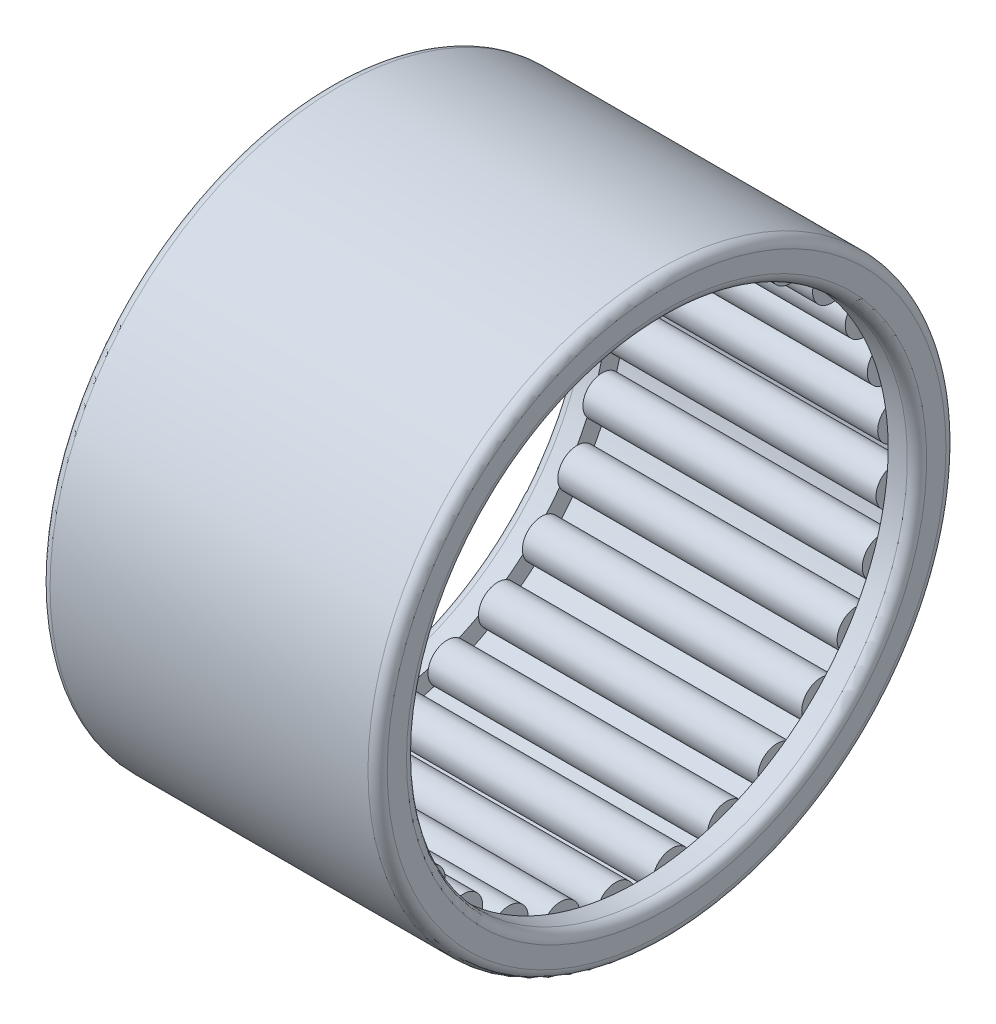
SolidWorks part; units mm, degrees
material "Plain Carbon Steel"
ref_plane "Front Plane" through (0, 0, 0) normal (0, 0, 1) x (1, 0, 0)
ref_plane "Top Plane" through (0, 0, 0) normal (0, 1, 0) x (1, 0, 0)
ref_plane "Right Plane" through (0, 0, 0) normal (1, 0, 0) x (0, 0, -1)
sketch "Sketch1" plane through (0, 0, 0) normal (0, 0, 1) x (1, 0, 0)
  line L0 (-17.5, 26) -> (-17.5, 30)
  line L1 (-17.5, 30) -> (17.5, 30)
  line L2 (17.5, 30) -> (17.5, 26)
  line L3 (17.5, 26) -> (14.5, 26)
  line L4 (14.5, 26) -> (14.5, 28)
  line L5 (14.5, 28) -> (-14.5, 28)
  line L6 (-14.5, 28) -> (-14.5, 26)
  line L7 (-14.5, 26) -> (-17.5, 26)
  line L8 (0, 0) -> (33.7186, 0) construction
  point P7 (0, 30)
  dimension "D1" = 4
  dimension "D2" = 35
  dimension "D3" = 4
  dimension "D4" = 3
  dimension "D5" = 2
  dimension "D6" = 30
  dimension "D7" = 3
revolve "Revolve1" add sketch "Sketch1" angle 360 about L8
fillet "Fillet1" radius 1 4 edges at (-17.5, 0, 30) (-17.5, 0, 26) (17.5, 0, 26) (17.5, 0, 30)
scale "Scale1" bodies to scale 103 120 114 108 125 102 119 113 107 124 101 130 118 112 129 106 123 117 111 128 105 122 116 110 127 104 121 115 109 126 scale about centroid uniform scaling yes scale factor 0.625
sketch "Sketch6" plane through (0, 0, 0) normal (1, 0, 0) x (0, 0, -1)
  line L0 (0, 0) -> (-16.8673, 0.5111) construction
  circle A0 centre (-16.8673, 0.5111) radius 1.25
  circle A1 centre (0, 0) radius 16.875 construction
  circle A2 centre (-16.363, 4.1251) radius 1.25
  circle A3 centre (-15.0937, 7.5462) radius 1.25
  circle A4 centre (-13.1186, 10.6145) radius 1.25
  circle A5 centre (-10.5301, 13.1864) radius 1.25
  circle A6 centre (-7.4492, 15.1418) radius 1.25
  circle A7 centre (-4.02, 16.3892) radius 1.25
  circle A8 centre (-0.4029, 16.8702) radius 1.25
  circle A9 centre (3.2332, 16.5624) radius 1.25
  circle A10 centre (6.718, 15.4801) radius 1.25
  circle A11 centre (9.8887, 13.674) radius 1.25
  circle A12 centre (12.597, 11.2286) radius 1.25
  circle A13 centre (14.7163, 8.2581) radius 1.25
  circle A14 centre (16.1475, 4.9014) radius 1.25
  circle A15 centre (16.8236, 1.3156) radius 1.25
  circle A16 centre (16.7131, -2.3317) radius 1.25
  circle A17 centre (15.8211, -5.8701) radius 1.25
  circle A18 centre (14.1893, -9.1339) radius 1.25
  circle A19 centre (11.8941, -11.9706) radius 1.25
  circle A20 centre (9.0427, -14.2476) radius 1.25
  circle A21 centre (5.7684, -15.8585) radius 1.25
  circle A22 centre (2.2245, -16.7277) radius 1.25
  circle A23 centre (-1.4235, -16.8149) radius 1.25
  circle A24 centre (-5.0049, -16.1157) radius 1.25
  circle A25 centre (-8.3523, -14.663) radius 1.25
  circle A26 centre (-11.3091, -12.5247) radius 1.25
  circle A27 centre (-13.7372, -9.8008) radius 1.25
  circle A28 centre (-15.5229, -6.6185) radius 1.25
  circle A29 centre (-16.5828, -3.1268) radius 1.25
  point P66 (0, 0)
  dimension "D1" = 29
extrude "Boss-Extrude1" add sketch "Sketch6" along normal up to surface (9.0625 mm away) and the other way up to surface (9.0625 mm away) up to face at (9.0625, 0, 16.25) other way up to face at (-9.0625, 0, 17.5)
